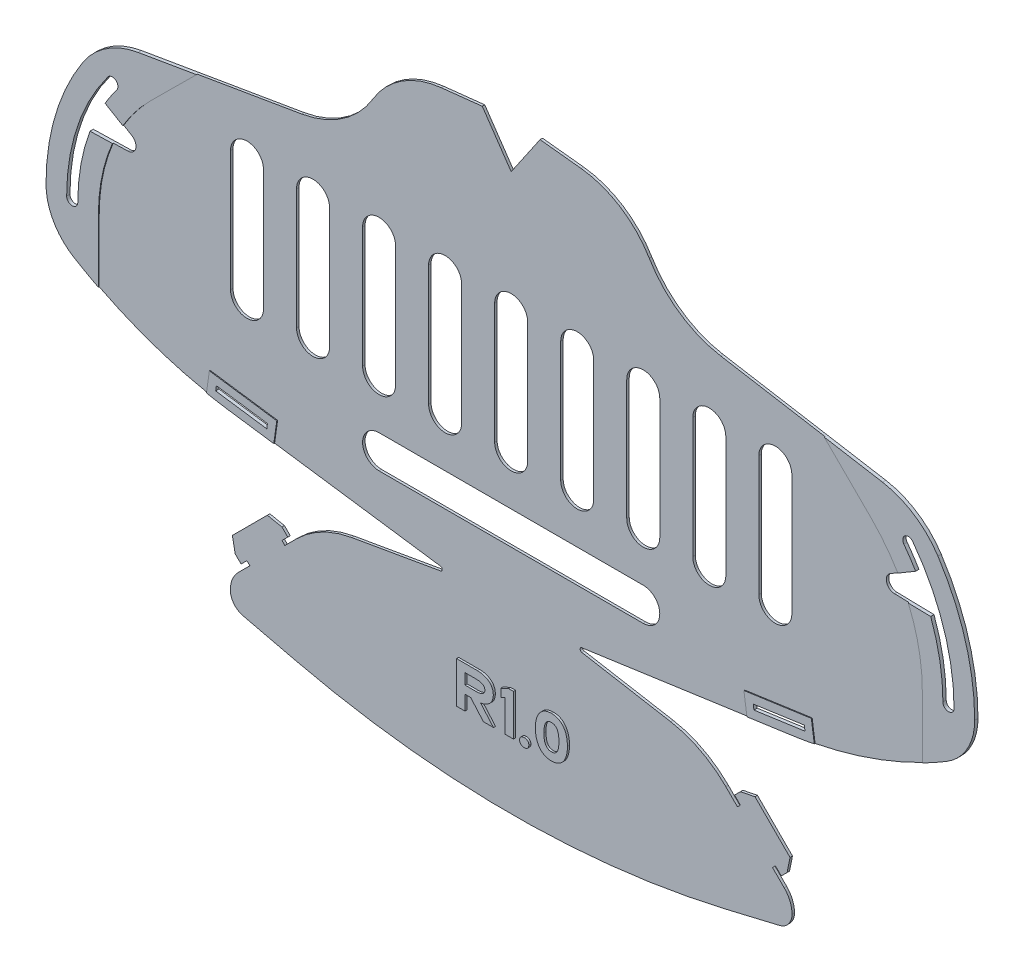
SolidWorks part; units mm, degrees
ref_plane "Front Plane" through (0, 0, 0) normal (0, 0, 1) x (1, 0, 0)
ref_plane "Top Plane" through (0, 0, 0) normal (0, 1, 0) x (1, 0, 0)
ref_plane "Right Plane" through (0, 0, 0) normal (1, 0, 0) x (0, 0, -1)
sketch "Sketch1" plane through (0, 0, 0) normal (0, 0, 1) x (1, 0, 0)
  line L0 (0, 0) -> (0, -145) construction
  line L1 (-14, -102) -> (14, -102) construction
  line L2 (-112.5, -69) -> (112.5, -69) construction
  line L3 (0, -10.2352) -> (-7, 0)
  line L4 (0, -10.2352) -> (7, 0)
  line L5 (7, 0) -> (16.9419, -1.0768)
  line L6 (-90.1804, -30.1909) -> (-50.7439, -23.5)
  line L7 (90.1804, -30.1909) -> (50.7439, -23.5)
  line L8 (-14, -102) -> (-68.2662, -94.2919)
  line L9 (-7, 0) -> (-16.9419, -1.0768)
  line L10 (14, -102) -> (68.2662, -94.2919)
  line L11 (-103.5977, -39) -> (-103.5977, -69) construction
  line L12 (-14, -102) -> (-38.6266, -106.305)
  line L13 (-52, -113.2546) -> (-54.8283, -116.0832)
  line L14 (52, -113.2546) -> (54.8283, -116.0832)
  line L15 (14, -102) -> (38.6266, -106.305)
  line L16 (-54.8283, -116.0832) -> (-55.5354, -115.3761)
  line L17 (-55.5354, -115.3761) -> (-54.1213, -113.9618)
  line L18 (-54.1213, -113.9618) -> (-55.5356, -112.5476)
  line L19 (-55.5356, -112.5476) -> (-59.0711, -111.8407)
  line L20 (-59.0711, -111.8407) -> (-67.556, -120.3263)
  line L21 (-64.0204, -123.8617) -> (-63.3132, -124.5688)
  line L22 (-63.3132, -124.5688) -> (-66.1415, -127.3973)
  line L23 (-64.0204, -123.8617) -> (-65.4345, -125.276)
  line L24 (-65.4345, -125.276) -> (-66.8488, -123.8618)
  line L25 (-67.556, -120.3263) -> (-66.8488, -123.8618)
  line L26 (67.556, -120.3263) -> (66.8488, -123.8618)
  line L27 (65.4345, -125.276) -> (66.8488, -123.8618)
  line L28 (64.0204, -123.8617) -> (65.4345, -125.276)
  line L29 (63.3132, -124.5688) -> (66.1415, -127.3973)
  line L30 (64.0204, -123.8617) -> (63.3132, -124.5688)
  line L31 (59.0711, -111.8407) -> (67.556, -120.3263)
  line L32 (55.5356, -112.5476) -> (59.0711, -111.8407)
  line L33 (54.1213, -113.9618) -> (55.5356, -112.5476)
  line L34 (55.5354, -115.3761) -> (54.1213, -113.9618)
  line L35 (54.8283, -116.0832) -> (55.5354, -115.3761)
  line L36 (-64.9691, -135.8852) -> (-52.4361, -138.8607)
  line L37 (64.9691, -135.8852) -> (52.4361, -138.8607)
  line L38 (-67.556, -120.3263) -> (-64.0204, -123.8617) construction
  line L39 (-59.0711, -111.8407) -> (-55.5354, -115.3761) construction
  arc A0 (-16.9419, -1.0768) -> (-33.4614, -11.6696) centre (-14.5729, -22.9489) ccw
  arc A1 (-33.4614, -11.6696) -> (-50.7439, -23.5) centre (-54.9257, 1.1478) cw
  arc A2 (-103.5977, -39) -> (-90.1804, -30.1909) centre (-86.8349, -49.9091) cw
  arc A3 (-112.5, -69) -> (-103.5977, -39) centre (-57.5, -69) cw
  arc A4 (112.5, -69) -> (103.5977, -39) centre (57.5, -69) ccw
  arc A5 (103.5977, -39) -> (90.1804, -30.1909) centre (86.8349, -49.9091) ccw
  arc A6 (16.9419, -1.0768) -> (33.4614, -11.6696) centre (14.5729, -22.9489) cw
  arc A7 (33.4614, -11.6696) -> (50.7439, -23.5) centre (54.9257, 1.1478) ccw
  arc A8 (-112.5, -69) -> (-105.7111, -81) centre (-98.5, -69) ccw
  arc A9 (-105.7111, -81) -> (-68.2662, -94.2919) centre (-54.2032, 4.7143) ccw
  arc A10 (112.5, -69) -> (105.7111, -81) centre (98.5, -69) cw
  arc A11 (105.7111, -81) -> (68.2662, -94.2919) centre (54.2032, 4.7143) cw
  arc A12 (-38.6266, -106.305) -> (-52, -113.2546) centre (-34.3216, -130.9315) ccw
  arc A13 (38.6266, -106.305) -> (52, -113.2546) centre (34.3216, -130.9315) cw
  arc A14 (-66.1415, -127.3973) -> (-68.0451, -131.9933) centre (-61.5451, -131.9933) ccw
  arc A15 (-68.0451, -131.9933) -> (-64.9691, -135.8852) centre (-64.0451, -131.9933) ccw
  arc A16 (68.0451, -131.9933) -> (64.9691, -135.8852) centre (64.0451, -131.9933) cw
  arc A17 (66.1415, -127.3973) -> (68.0451, -131.9933) centre (61.5451, -131.9933) cw
  arc A19 (-52.4361, -138.8607) -> (0, -145) centre (0, 82) ccw
  arc A20 (52.4361, -138.8607) -> (0, -145) centre (0, 82) cw
  point P8 (0, -102)
  point P11 (0, -69)
  dimension "D5" = 55
  dimension "D11" = 20
  dimension "D13" = 25
  dimension "D16" = 14
  dimension "D15" = 22
  dimension "D18" = 100
  dimension "D22" = 25
  dimension "D31" = 6.5
  dimension "D32" = 4
  dimension "D34" = 227
  dimension "D1" = 145
  dimension "D2" = 28
  dimension "D3" = 43
  dimension "D4" = 76
  dimension "D6" = 225
  dimension "D7" = 14
  dimension "D8" = 12.4
  dimension "D9" = 10
  dimension "D10" = 30
  dimension "D12" = 40
  dimension "D14" = 45.5
  dimension "D17" = 12
  dimension "D19" = 18
  dimension "D20" = 25
  dimension "D21" = 4
  dimension "D23" = 38
  dimension "D24" = 1
  dimension "D25" = 2
  dimension "D26" = 2
  dimension "D27" = 12
  dimension "D29" = 6
  dimension "D30" = 4
extrude "Main Shape" add sketch "Sketch1" along normal blind 0.6
sketch "Sketch2" plane through (0, 0, 0.6) normal (0, 0, 1) x (1, 0, 0)
  line L0 (0, -55) -> (0, 55) construction
  arc A0 (-96.42, -39.81) -> (-106.15, -69) centre (-57.5, -69) ccw construction
  arc A1 (-97.5, -39) -> (-107.5, -69) centre (-57.5, -69) ccw
  arc A2 (-95.34, -40.62) -> (-104.8, -69) centre (-57.5, -69) ccw
  arc A3 (-95.34, -40.62) -> (-97.5, -39) centre (-96.42, -39.81) ccw
  arc A4 (-107.5, -69) -> (-104.8, -69) centre (-106.15, -69) ccw
  arc A6 (-103.5977, -39) -> (-112.5, -69) centre (-57.5, -69) ccw construction
  arc A7 (96.42, -39.81) -> (106.15, -69) centre (57.5, -69) cw construction
  arc A8 (97.5, -39) -> (107.5, -69) centre (57.5, -69) cw
  arc A9 (95.34, -40.62) -> (104.8, -69) centre (57.5, -69) cw
  arc A10 (95.34, -40.62) -> (97.5, -39) centre (96.42, -39.81) cw
  arc A11 (107.5, -69) -> (104.8, -69) centre (106.15, -69) cw
  point P3 (-103.6534, -53.6155)
  point P19 (103.6534, -53.6155)
  dimension "D1" = 5
  dimension "D2" = 1.35
extrude "Elastic Attachment Points" cut sketch "Sketch2" against normal through all
sketch "Sketch7" plane through (0, 0, 0.6) normal (0, 0, 1) x (1, 0, 0)
  line L0 (-99.8, -69) -> (-99.8, -84.2853)
  line L1 (-87.321, -39) -> (-76.0466, -27.7929)
  line L2 (-50.7439, -23.5) -> (-90.1804, -30.1909) construction
  line L3 (-76.0466, -27.7929) -> (-90.1804, -30.1909)
  line L4 (0, -55) -> (0, 55) construction
  line L5 (76.0466, -27.7929) -> (90.1804, -30.1909)
  line L6 (87.321, -39) -> (76.0466, -27.7929)
  line L7 (99.8, -69) -> (99.8, -84.2853)
  arc A0 (-99.8, -69) -> (-87.321, -39) centre (-57.5, -69) cw
  arc A1 (-95.34, -40.62) -> (-104.8, -69) centre (-57.5, -69) ccw construction
  arc A2 (-105.7111, -81) -> (-68.2662, -94.2919) centre (-54.2032, 4.7143) ccw construction
  arc A3 (-112.5, -69) -> (-105.7111, -81) centre (-98.5, -69) ccw construction
  arc A4 (-103.5977, -39) -> (-112.5, -69) centre (-57.5, -69) ccw construction
  arc A5 (-90.1804, -30.1909) -> (-103.5977, -39) centre (-86.8349, -49.9091) ccw construction
  arc A6 (-105.7111, -81) -> (-99.8, -84.2853) centre (-54.2032, 4.7143) ccw
  arc A7 (-112.5, -69) -> (-105.7111, -81) centre (-98.5, -69) ccw
  arc A8 (-103.5977, -39) -> (-112.5, -69) centre (-57.5, -69) ccw
  arc A9 (-90.1804, -30.1909) -> (-103.5977, -39) centre (-86.8349, -49.9091) ccw
  arc A10 (90.1804, -30.1909) -> (103.5977, -39) centre (86.8349, -49.9091) cw
  arc A11 (103.5977, -39) -> (112.5, -69) centre (57.5, -69) cw
  arc A12 (112.5, -69) -> (105.7111, -81) centre (98.5, -69) cw
  arc A13 (105.7111, -81) -> (99.8, -84.2853) centre (54.2032, 4.7143) cw
  arc A14 (99.8, -69) -> (87.321, -39) centre (57.5, -69) ccw
  arc A15 (-107.5, -69) -> (-104.8, -69) centre (-106.15, -69) ccw construction
  arc A16 (-95.34, -40.62) -> (-97.5, -39) centre (-96.42, -39.81) ccw construction
  arc A17 (-97.5, -39) -> (-107.5, -69) centre (-57.5, -69) ccw construction
  arc A18 (-107.5, -69) -> (-104.8, -69) centre (-106.15, -69) ccw
  arc A19 (-95.34, -40.62) -> (-97.5, -39) centre (-96.42, -39.81) ccw
  arc A20 (-95.34, -40.62) -> (-104.8, -69) centre (-57.5, -69) ccw
  arc A21 (-97.5, -39) -> (-107.5, -69) centre (-57.5, -69) ccw
  arc A22 (104.8, -69) -> (107.5, -69) centre (106.15, -69) ccw construction
  arc A23 (97.5, -39) -> (95.34, -40.62) centre (96.42, -39.81) ccw construction
  arc A24 (104.8, -69) -> (95.34, -40.62) centre (57.5, -69) ccw construction
  arc A25 (107.5, -69) -> (97.5, -39) centre (57.5, -69) ccw construction
  arc A26 (104.8, -69) -> (107.5, -69) centre (106.15, -69) ccw
  arc A27 (97.5, -39) -> (95.34, -40.62) centre (96.42, -39.81) ccw
  arc A28 (104.8, -69) -> (95.34, -40.62) centre (57.5, -69) ccw
  arc A29 (107.5, -69) -> (97.5, -39) centre (57.5, -69) ccw
  dimension "D1" = 5
extrude "Reinforced Attachment Points" add sketch "Sketch7" along normal blind 0.2
sketch "Sketch6" plane through (0, 0, 0.6) normal (0, 0, 1) x (1, 0, 0)
  line L0 (-71.3899, -91.8282) -> (-59.0141, -93.5861)
  line L1 (-59.0141, -93.5861) -> (-58.8453, -92.398)
  line L2 (-58.8453, -92.398) -> (-71.2211, -90.6401)
  line L3 (-71.2211, -90.6401) -> (-71.3899, -91.8282)
  line L4 (-68.2662, -94.2919) -> (-14, -102) construction
  line L5 (-65.0332, -91.519) -> (-65.202, -92.7071) construction
  line L13 (0, -55) -> (0, 55) construction
  line L14 (65.0332, -91.519) -> (65.202, -92.7071) construction
  line L15 (71.3899, -91.8282) -> (71.2211, -90.6401)
  line L16 (58.8453, -92.398) -> (59.0141, -93.5861)
  line L22 (58.8453, -92.398) -> (71.2211, -90.6401)
  line L24 (71.3899, -91.8282) -> (59.0141, -93.5861)
  dimension "D1" = 2
  dimension "D2" = 12.5
  dimension "D3" = 52
  dimension "D4" = 1.2
extrude "Tab Slits" cut sketch "Sketch6" against normal through all
sketch "Sketch9" plane through (0, 0, 0.6) normal (0, 0, 1) x (1, 0, 0)
  line L4 (-59.0141, -93.5861) -> (-58.8453, -92.398) construction
  line L5 (-71.3899, -91.8282) -> (-59.0141, -93.5861) construction
  line L6 (-71.2211, -90.6401) -> (-71.3899, -91.8282) construction
  line L7 (-58.8453, -92.398) -> (-71.2211, -90.6401) construction
  line L12 (-59.0141, -93.5861) -> (-58.8453, -92.398)
  line L13 (-71.3899, -91.8282) -> (-59.0141, -93.5861)
  line L14 (-71.2211, -90.6401) -> (-71.3899, -91.8282)
  line L15 (-58.8453, -92.398) -> (-71.2211, -90.6401)
  line L16 (-57.3152, -95.8474) -> (-56.5839, -90.6991)
  line L17 (-68.2662, -94.2919) -> (-14, -102) construction
  line L18 (-56.5839, -90.6991) -> (-72.92, -88.3787)
  line L19 (-72.92, -88.3787) -> (-73.6304, -93.3805)
  line L20 (-68.2662, -94.2919) -> (-57.3152, -95.8474)
  line L21 (0, -55) -> (0, 55) construction
  line L22 (68.2662, -94.2919) -> (57.3152, -95.8474)
  line L23 (72.92, -88.3787) -> (73.6304, -93.3805)
  line L24 (56.5839, -90.6991) -> (72.92, -88.3787)
  line L25 (57.3152, -95.8474) -> (56.5839, -90.6991)
  line L26 (58.8453, -92.398) -> (71.2211, -90.6401)
  line L27 (71.2211, -90.6401) -> (71.3899, -91.8282)
  line L28 (71.3899, -91.8282) -> (59.0141, -93.5861)
  line L29 (59.0141, -93.5861) -> (58.8453, -92.398)
  arc A0 (-99.8, -84.2853) -> (-68.2662, -94.2919) centre (-54.2032, 4.7143) ccw construction
  arc A1 (-73.6304, -93.3805) -> (-68.2662, -94.2919) centre (-54.2032, 4.7143) ccw
  arc A2 (73.6304, -93.3805) -> (68.2662, -94.2919) centre (54.2032, 4.7143) cw
  dimension "D1" = 2
  dimension "D2" = 2
  dimension "D3" = 2
extrude "Reinforced Tab Slits" add sketch "Sketch9" along normal blind 0.2
sketch "Sketch3" plane through (0, 0, 0.6) normal (0, 0, 1) x (1, 0, 0)
  line L3 (0, -10.2352) -> (0, -145) construction
  line L4 (-106.15, -69) -> (-96.42, -69) construction
  line L5 (-96.42, -69) -> (-96.42, -39.81) construction
  line L427 (0, -39.81) -> (0, -69) construction
  line L428 (4, -39.81) -> (4, -69)
  line L429 (-4, -39.81) -> (-4, -69)
  line L444 (-16, -39.81) -> (-16, -69) construction
  line L447 (-12, -39.81) -> (-12, -69)
  line L450 (-20, -39.81) -> (-20, -69)
  line L451 (-32, -39.81) -> (-32, -69) construction
  line L455 (-28, -39.81) -> (-28, -69)
  line L456 (-36, -39.81) -> (-36, -69)
  line L836 (-32, -85) -> (32, -85) construction
  line L837 (-32, -81) -> (32, -81)
  line L838 (-32, -89) -> (32, -89)
  line L839 (-64, -73) -> (64, -73) construction
  line L933 (-48, -39.81) -> (-48, -69) construction
  line L934 (-44, -39.81) -> (-44, -69)
  line L935 (-52, -39.81) -> (-52, -69)
  line L936 (-64, -39.81) -> (-64, -69) construction
  line L937 (-60, -39.81) -> (-60, -69)
  line L938 (-68, -39.81) -> (-68, -69)
  line L939 (16, -39.81) -> (16, -69) construction
  line L940 (12, -39.81) -> (12, -69)
  line L941 (20, -39.81) -> (20, -69)
  line L942 (32, -39.81) -> (32, -69) construction
  line L943 (28, -39.81) -> (28, -69)
  line L944 (36, -39.81) -> (36, -69)
  line L945 (48, -39.81) -> (48, -69) construction
  line L946 (44, -39.81) -> (44, -69)
  line L947 (52, -39.81) -> (52, -69)
  line L948 (64, -39.81) -> (64, -69) construction
  line L949 (60, -39.81) -> (60, -69)
  line L950 (68, -39.81) -> (68, -69)
  arc A2 (-52.4361, -138.8607) -> (52.4361, -138.8607) centre (0, 82) ccw construction
  arc A21 (4, -39.81) -> (-4, -39.81) centre (0, -39.81) ccw
  arc A22 (-4, -69) -> (4, -69) centre (0, -69) ccw
  arc A23 (-12, -39.81) -> (-20, -39.81) centre (-16, -39.81) ccw
  arc A24 (-20, -69) -> (-12, -69) centre (-16, -69) ccw
  arc A25 (-28, -39.81) -> (-36, -39.81) centre (-32, -39.81) ccw
  arc A26 (-36, -69) -> (-28, -69) centre (-32, -69) ccw
  arc A27 (-44, -39.81) -> (-52, -39.81) centre (-48, -39.81) ccw
  arc A28 (-52, -69) -> (-44, -69) centre (-48, -69) ccw
  arc A29 (-60, -39.81) -> (-68, -39.81) centre (-64, -39.81) ccw
  arc A30 (-68, -69) -> (-60, -69) centre (-64, -69) ccw
  arc A31 (12, -39.81) -> (20, -39.81) centre (16, -39.81) cw
  arc A32 (20, -69) -> (12, -69) centre (16, -69) cw
  arc A33 (28, -39.81) -> (36, -39.81) centre (32, -39.81) cw
  arc A34 (36, -69) -> (28, -69) centre (32, -69) cw
  arc A35 (44, -39.81) -> (52, -39.81) centre (48, -39.81) cw
  arc A36 (52, -69) -> (44, -69) centre (48, -69) cw
  arc A37 (60, -39.81) -> (68, -39.81) centre (64, -39.81) cw
  arc A38 (68, -69) -> (60, -69) centre (64, -69) cw
  arc A39 (-32, -81) -> (-32, -89) centre (-32, -85) ccw
  arc A40 (32, -89) -> (32, -81) centre (32, -85) ccw
  point P3 (-16, -54.405)
  point P18 (-32, -54.405)
  point P30 (-48, -54.405)
  point P37 (-64, -54.405)
  point P43 (16, -54.405)
  point P50 (32, -54.405)
  point P57 (48, -54.405)
  point P64 (64, -54.405)
  point P71 (0, -85)
  point P414 (0, -54.405)
  dimension "D5" = 8
  dimension "D1" = 8
  dimension "D2" = 5
  dimension "D3" = 8
  dimension "D4" = 8
extrude "Breathing Slits" cut sketch "Sketch3" against normal through all
sketch "Sketch8" plane through (0, 0, 0.6) normal (0, 0, 1) x (1, 0, 0)
  line L0 (-67.0266, -128.5) -> (67.0266, -128.5) construction
  line L1 (0, -10.2352) -> (0, -145) construction
  arc A0 (-52.4361, -138.8607) -> (52.4361, -138.8607) centre (0, 82) ccw construction
  arc A1 (-66.1415, -127.3973) -> (-68.0451, -131.9933) centre (-61.5451, -131.9933) ccw construction
  text T0 "<b>R1.0</b>" font "Double Porter 3" height 10
  point P9 (0, -128.5)
  dimension "D2" = 16.5
extrude "Version Number" add sketch "Sketch8" along normal blind 0.5
fillet "Fillet1" radius 0.5 2 edges at (-14, -102, 0.3) (14, -102, 0.3)
sketch "Sketch12" plane through (0, 0, 0.8) normal (0, 0, 1) x (1, 0, 0)
  line L0 (-98.1829, -44.8713) -> (-91.8731, -48.6136)
  line L1 (-98.1829, -44.8713) -> (-89.3972, -30.058) construction
  line L2 (-76.0466, -27.7929) -> (-90.1804, -30.1909) construction
  line L3 (-101.8445, -52.5422) -> (-92.8469, -52.3333)
  line L4 (0, -55) -> (0, 55) construction
  line L5 (98.1829, -44.8713) -> (89.3972, -30.058) construction
  line L6 (101.8445, -52.5422) -> (92.8469, -52.3333)
  line L7 (98.1829, -44.8713) -> (91.8731, -48.6136)
  arc A0 (-95.34, -40.62) -> (-104.8, -69) centre (-57.5, -69) ccw construction
  arc A1 (-92.8469, -52.3333) -> (-91.8731, -48.6136) centre (-92.8933, -50.3338) ccw
  arc A2 (-98.1829, -44.8713) -> (-101.8445, -52.5422) centre (-57.5, -69) ccw
  arc A3 (98.1829, -44.8713) -> (101.8445, -52.5422) centre (57.5, -69) cw
  arc A4 (92.8469, -52.3333) -> (91.8731, -48.6136) centre (92.8933, -50.3338) cw
  dimension "D4" = 2
  dimension "D1" = 24.1287
  dimension "D2" = 8.5
  dimension "D3" = 9
extrude "Cut-Extrude1" cut sketch "Sketch12" against normal through all both and the other way through all
